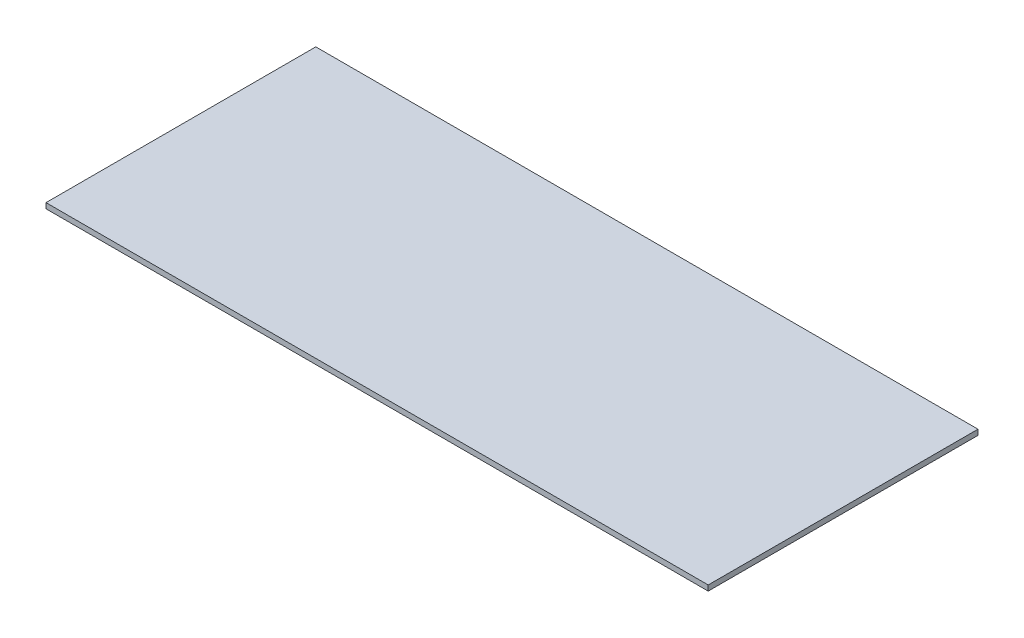
SolidWorks part; units mm, degrees
material "Pine"
ref_plane "Front Plane" through (0, 0, 0) normal (0, 0, 1) x (1, 0, 0)
ref_plane "Top Plane" through (0, 0, 0) normal (0, 1, 0) x (1, 0, 0)
ref_plane "Right Plane" through (0, 0, 0) normal (1, 0, 0) x (0, 0, -1)
sketch "Sketch1" plane through (0, 0, 0) normal (0, 1, 0) x (1, 0, 0)
  line L1 (-342.9, -139.7) -> (342.9, -139.7)
  line L2 (-342.9, -139.7) -> (-342.9, 139.7)
  line L3 (-342.9, 139.7) -> (342.9, 139.7)
  line L4 (342.9, -139.7) -> (342.9, 139.7)
  line L5 (-342.9, -139.7) -> (342.9, 139.7) construction
  line L6 (-342.9, 139.7) -> (342.9, -139.7) construction
  point P0 (0, 0)
  dimension "D1" = 279.4
  dimension "D2" = 685.8
extrude "Boss-Extrude1" add sketch "Sketch1" along normal blind 5.5562
